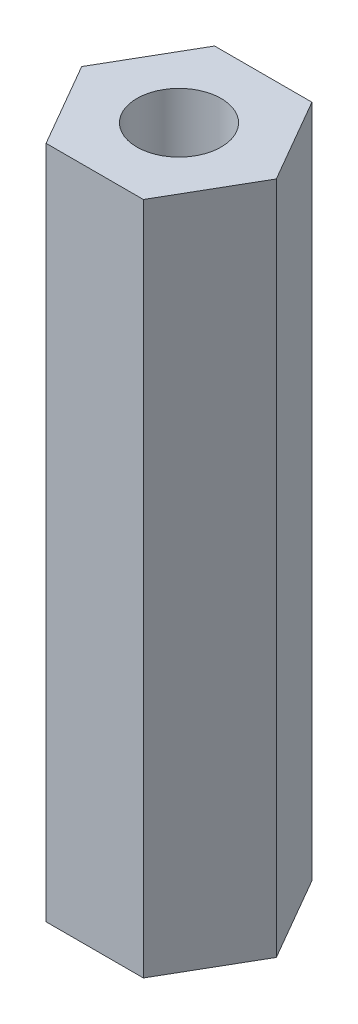
SolidWorks part; units mm, degrees
ref_plane "前视基准面" through (0, 0, 0) normal (0, 0, 1) x (1, 0, 0)
ref_plane "上视基准面" through (0, 0, 0) normal (0, 1, 0) x (1, 0, 0)
ref_plane "右视基准面" through (0, 0, 0) normal (1, 0, 0) x (0, 0, -1)
ref_plane "基准面4" through (0, 0, 0) normal (0, -1, 0) x (1, 0, 0)
sketch "草图1" plane through (0, 0, 0) normal (0, -1, 0) x (1, 0, 0)
  line L0 (-1.4434, -2.5) -> (1.4434, -2.5)
  line L1 (1.4434, -2.5) -> (2.8868, 0)
  line L2 (2.8868, 0) -> (1.4434, 2.5)
  line L3 (1.4434, 2.5) -> (-1.4434, 2.5)
  line L4 (-1.4434, 2.5) -> (-2.8868, 0)
  line L5 (-2.8868, 0) -> (-1.4434, -2.5)
  circle A0 centre (0, 0) radius 1.25
extrude "凸台-拉伸1" add sketch "草图1" against normal blind 20
